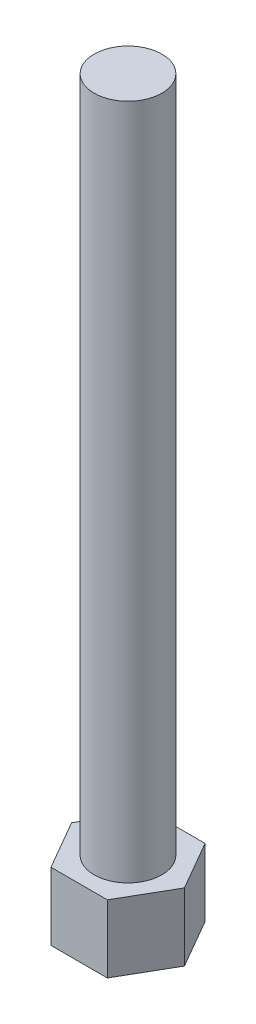
SolidWorks part; units mm, degrees
ref_plane "Front Plane" through (0, 0, 0) normal (0, 0, 1) x (1, 0, 0)
ref_plane "Top Plane" through (0, 0, 0) normal (0, 1, 0) x (1, 0, 0)
ref_plane "Right Plane" through (0, 0, 0) normal (1, 0, 0) x (0, 0, -1)
sketch "Sketch1" plane through (0, 0, 0) normal (0, 1, 0) x (1, 0, 0)
  circle A0 centre (0, 0) radius 1.5
  dimension "D1" = 3
extrude "Boss-Extrude1" add sketch "Sketch1" along normal blind 30
cosmetic thread "Cosmetic Thread2"
sketch "Sketch2" plane through (0, 0, 0) normal (0, -1, 0) x (1, 0, 0)
  line L1 (1.25, -2.1651) -> (2.5, 0)
  line L2 (2.5, 0) -> (1.25, 2.1651)
  line L3 (1.25, 2.1651) -> (-1.25, 2.1651)
  line L4 (-1.25, 2.1651) -> (-2.5, 0)
  line L5 (-2.5, 0) -> (-1.25, -2.1651)
  line L6 (-1.25, -2.1651) -> (1.25, -2.1651)
  circle A0 centre (0, 0) radius 2.1651 construction
  dimension "D1" = 2.5
extrude "Boss-Extrude2" add sketch "Sketch2" along normal blind 3
cosmetic thread "Cosmetic Thread1"
